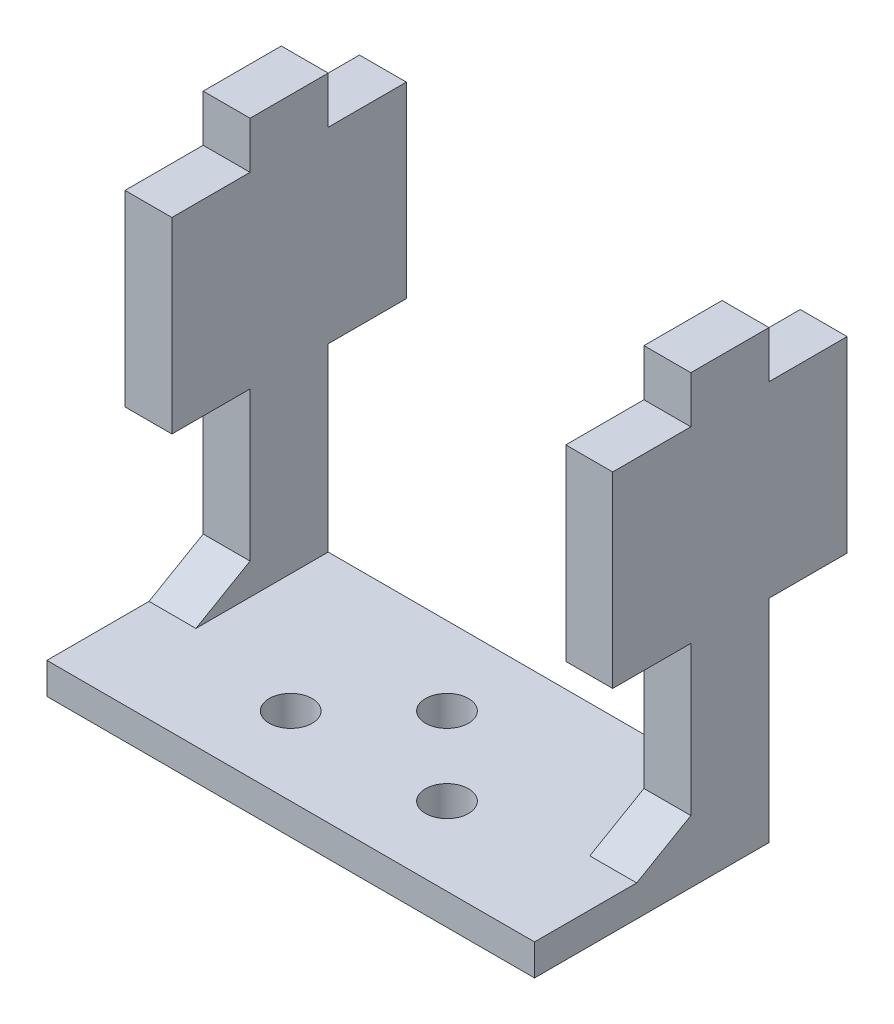
SolidWorks part; units mm, degrees
ref_plane "Front Plane" through (0, 0, 0) normal (0, 0, 1) x (1, 0, 0)
ref_plane "Top Plane" through (0, 0, 0) normal (0, 1, 0) x (1, 0, 0)
ref_plane "Right Plane" through (0, 0, 0) normal (1, 0, 0) x (0, 0, -1)
sketch "Sketch1" plane through (0, 0, 0) normal (0, 1, 0) x (1, 0, 0)
  line L1 (0, 0) -> (31.2, 0)
  line L2 (0, 0) -> (0, 15)
  line L3 (0, 15) -> (31.2, 15)
  line L4 (31.2, 0) -> (31.2, 15)
  circle A0 centre (15.6, 10) radius 1.375
  circle A1 centre (10.6, 5) radius 1.375
  circle A2 centre (20.6, 5) radius 1.375
  point P11 (0, 0)
  point P12 (0, 0)
  point P13 (15.6, 15)
  point P14 (15, 11.5122)
  dimension "D7" = 2.75
  dimension "D1" = 31.2
  dimension "D2" = 15
  dimension "D3" = 5
  dimension "D4" = 5
extrude "Boss-Extrude1" add sketch "Sketch1" along normal blind 2
sketch "Sketch2" plane through (0, 2, 0) normal (0, 1, 0) x (1, 0, 0)
  line L1 (0, 15) -> (3, 15)
  line L2 (0, 15) -> (0, 10)
  line L3 (0, 10) -> (3, 10)
  line L4 (3, 15) -> (3, 10)
  line L5 (31.2, 15) -> (28.2, 15)
  line L6 (31.2, 15) -> (31.2, 10)
  line L7 (31.2, 10) -> (28.2, 10)
  line L8 (28.2, 15) -> (28.2, 10)
  dimension "D1" = 5
  dimension "D2" = 3
extrude "Boss-Extrude2" add sketch "Sketch2" along normal blind 26.54
sketch "Sketch3" plane through (0, 0, -15) normal (0, 0, -1) x (-1, 0, 0)
  line L0 (-31.2, 28.54) -> (-31.2, 0) construction
  line L1 (-31.2, 25.54) -> (-28.2, 25.54)
  line L2 (-31.2, 25.54) -> (-31.2, 13.54)
  line L3 (-31.2, 13.54) -> (-28.2, 13.54)
  line L4 (-28.2, 25.54) -> (-28.2, 13.54)
  line L5 (-28.2, 28.54) -> (-28.2, 2) construction
  line L6 (-31.2, 28.54) -> (-28.2, 28.54) construction
  line L7 (-3, 28.54) -> (-3, 2) construction
  line L8 (-3, 25.54) -> (0, 25.54)
  line L9 (-3, 25.54) -> (-3, 13.54)
  line L10 (-3, 13.54) -> (0, 13.54)
  line L11 (0, 25.54) -> (0, 13.54)
  line L12 (0, 28.54) -> (0, 0) construction
  dimension "D1" = 3
  dimension "D2" = 12
extrude "Boss-Extrude3" add sketch "Sketch3" along normal blind 5 and the other way blind 10 from surface at 0 contours L2 L1 L4 L3 | L9 L8 L11 L10 starting at face at (15.6, 14.77, -15)
sketch "Sketch5" plane through (31.2, 0, 0) normal (1, 0, 0) x (0, 0, -1)
  line L0 (10, 4) -> (6.5359, 2)
  line L1 (10, 13.54) -> (10, 2) construction
  line L3 (6.5359, 2) -> (10, 2)
  line L4 (0, 2) -> (10, 2) construction
  line L5 (10, 2) -> (10, 4)
  point P11 (0, 0)
  point P12 (10, 4.2686)
  dimension "D1" = 30
  dimension "D2" = 2
extrude "Boss-Extrude4" add sketch "Sketch5" against normal up to surface (3 mm away) up to face at (28.2, 18.1167, -12.5)
sketch "Sketch6" plane through (0, 0, 0) normal (1, 0, 0) x (0, 0, -1)
  line L0 (10, 4) -> (6.5359, 2)
  line L3 (6.5359, 2) -> (10, 2)
  line L5 (10, 2) -> (10, 4)
  line L6 (0, 2) -> (6.5359, 2) construction
  dimension "D1" = 30
  dimension "D2" = 2
extrude "Boss-Extrude5" add sketch "Sketch6" along normal up to surface (3 mm away) up to face at (3, 18.1167, -12.5)
